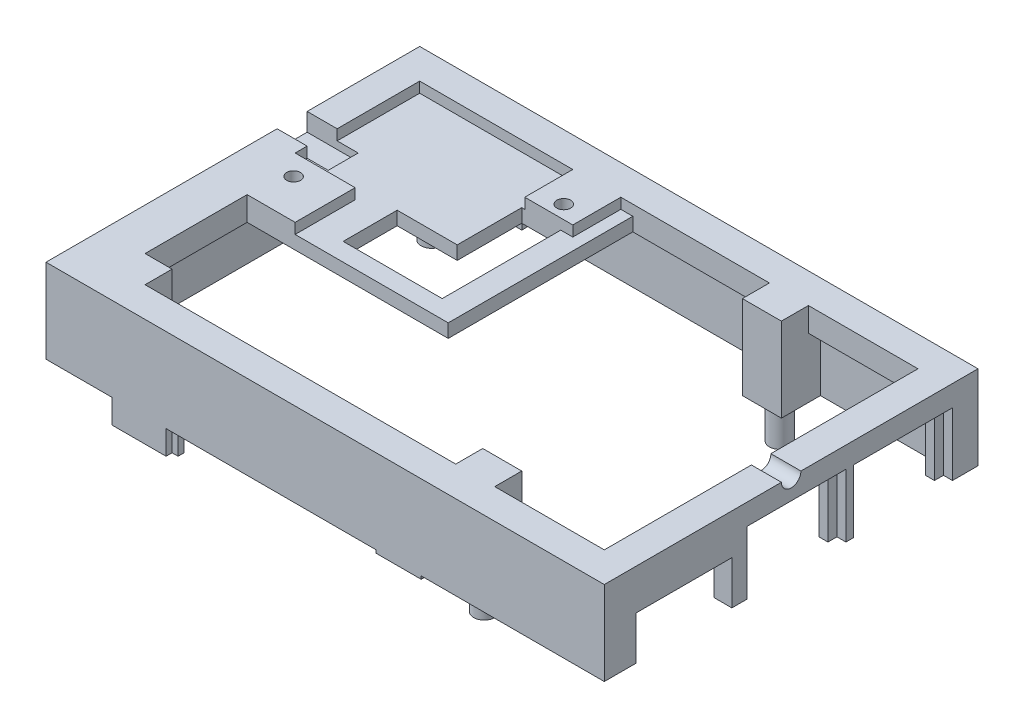
SolidWorks part; units mm, degrees
ref_plane "Front Plane" through (0, 0, 0) normal (0, 0, 1) x (1, 0, 0)
ref_plane "Top Plane" through (0, 0, 0) normal (0, 1, 0) x (1, 0, 0)
ref_plane "Right Plane" through (0, 0, 0) normal (1, 0, 0) x (0, 0, -1)
sketch "Sketch1" plane through (0, 0, 0) normal (0, 1, 0) x (1, 0, 0)
  line L1 (0, 0) -> (93, 0)
  line L2 (0, 0) -> (0, 62.25)
  line L3 (0, 62.25) -> (93, 62.25)
  line L4 (93, 0) -> (93, 62.25)
  line L5 (7, 5) -> (88, 5)
  line L7 (40.5, 57.25) -> (88, 57.25)
  line L8 (88, 5) -> (88, 57.25)
  line L13 (7, 26.5) -> (7, 5)
  line L14 (7, 26.5) -> (40.5, 26.5)
  line L15 (40.5, 26.5) -> (40.5, 57.25)
  dimension "D1" = 93
  dimension "D2" = 62.25
  dimension "D3" = 5
  dimension "D4" = 5
  dimension "D5" = 5
  dimension "D6" = 7
  dimension "D7" = 30.75
  dimension "D8" = 33.5
extrude "Boss-Extrude1" add sketch "Sketch1" along normal blind 4
sketch "Sketch5" plane through (0, 4, 0) normal (0, 1, 0) x (1, 0, 0)
  line L0 (88, 57.25) -> (40.5, 57.25) construction
  line L1 (40.5, 26.5) -> (15, 26.5)
  line L2 (40.5, 26.5) -> (40.5, 57.25)
  line L3 (40.5, 57.25) -> (38.5, 57.25)
  line L4 (5, 36.5) -> (5, 57.25)
  line L5 (5, 36.5) -> (15, 36.5)
  line L6 (15, 36.5) -> (15, 26.5)
  line L7 (30.5, 57.25) -> (5, 57.25)
  line L9 (30.5, 57.25) -> (30.5, 49.25)
  line L10 (30.5, 49.25) -> (38.5, 49.25)
  line L11 (38.5, 57.25) -> (38.5, 49.25)
  dimension "D1" = 35.5
  dimension "D2" = 10
  dimension "D3" = 2
  dimension "D4" = 8
extrude "Cut-Extrude1" cut sketch "Sketch5" against normal blind 1.75
sketch "Sketch6" plane through (0, 2.25, 0) normal (0, 1, 0) x (1, 0, 0)
  line L0 (38.5, 49.25) -> (30.5, 49.25) construction
  line L1 (30, 49.25) -> (36.5, 49.25)
  line L2 (30, 49.25) -> (30, 38.5)
  line L3 (28.25, 29.5) -> (36.5, 29.5)
  line L4 (36.5, 49.25) -> (36.5, 29.5)
  line L5 (36.5, 29.5) -> (20, 29.5)
  line L6 (36.5, 29.5) -> (36.5, 39.375)
  line L7 (30, 38.5) -> (20, 38.5)
  line L8 (20, 29.5) -> (20, 38.5)
  line L9 (20, 29.5) -> (28.25, 29.5)
  line M12 (38.5, 49.25) -> (30.5, 49.25)
  dimension "D1" = 2
  dimension "D2" = 19.75
  dimension "D3" = 16.5
  dimension "D4" = 9
  dimension "D5" = 10
extrude "Cut-Extrude2" cut sketch "Sketch6" against normal through all contours L8 L5 L3 L4 L1 L2 L7 M12
sketch "Sketch7" plane through (0, 4, 0) normal (0, 1, 0) x (1, 0, 0)
  line L0 (30.5, 57.25) -> (5, 57.25) construction
  line L1 (5, 57.25) -> (5, 36.5) construction
  circle A0 centre (8.25, 33) radius 1.15
  circle A1 centre (34.75, 51.5) radius 1.15
  dimension "D2" = 2.3
  dimension "D3" = 2.3
  dimension "D1" = 5.75
  dimension "D4" = 29.75
  dimension "D5" = 3.25
  dimension "D6" = 24.25
extrude "Cut-Extrude3" cut sketch "Sketch7" against normal through all
sketch "Sketch8" plane through (0, 0, 0) normal (0, -1, 0) x (1, 0, 0)
  line L0 (90, -3) -> (90, -59.25)
  line L1 (93, 0) -> (0, 0)
  line L2 (93, 0) -> (93, -62.25)
  line L3 (93, -62.25) -> (0, -62.25)
  line L4 (0, 0) -> (0, -62.25)
  line L5 (90, -59.25) -> (3, -59.25)
  line L6 (3, -3) -> (3, -59.25)
  line L7 (90, -3) -> (3, -3)
  line M11 (0, 0) -> (0, -62.25)
  line M12 (0, -62.25) -> (93, -62.25)
  line M13 (93, -62.25) -> (93, 0)
  line M14 (93, 0) -> (0, 0)
  dimension "D1" = 3
extrude "Boss-Extrude3" add sketch "Sketch8" along normal blind 10 contours L7 L0 L5 L6 M14 M11 M12 M13 | L2 L1 L4 L3
sketch "Sketch16" plane through (0, 4, 0) normal (0, 1, 0) x (1, 0, 0)
  line L0 (90, 3) -> (3, 3) construction
  line L1 (7, 5) -> (11.5, 5) construction
  line L2 (7, 5) -> (7, 9.5) construction
  line L3 (7, 9.5) -> (11.5, 9.5) construction
  line L4 (11.5, 5) -> (11.5, 9.5) construction
  line L5 (11.5, 9.5) -> (5, 9.5)
  line L6 (11.5, 9.5) -> (11.5, 3)
  line L7 (11.5, 3) -> (5, 3)
  line L8 (5, 9.5) -> (5, 3)
  line L9 (0, 31.125) -> (93, 31.125) construction
  line L10 (0, 0) -> (0, 62.25) construction
  line L12 (5, 52.75) -> (5, 59.25)
  line L13 (69.75, 9.5) -> (63.25, 9.5)
  line L14 (69.75, 9.5) -> (69.75, 3)
  line L15 (69.75, 3) -> (63.25, 3)
  line L16 (63.25, 9.5) -> (63.25, 3)
  line L17 (11.5, 59.25) -> (5, 59.25)
  line L18 (11.5, 52.75) -> (11.5, 59.25)
  line L19 (11.5, 52.75) -> (5, 52.75)
  line L20 (11.5, 57.25) -> (11.5, 52.75)
  line L21 (7, 52.75) -> (11.5, 52.75)
  line L22 (63.25, 52.75) -> (63.25, 59.25)
  line L23 (69.75, 59.25) -> (63.25, 59.25)
  line L24 (69.75, 52.75) -> (69.75, 59.25)
  line L25 (69.75, 52.75) -> (63.25, 52.75)
  line L26 (93, 0) -> (93, 62.25) construction
  line M4 (5, 36.5) -> (5, 57.25)
  line M11 (88, 5) -> (7, 5)
  line M12 (7, 5) -> (7, 26.5)
  line M43 (5, 57.25) -> (30.5, 57.25)
  line M47 (38.5, 57.25) -> (88, 57.25)
  dimension "D1" = 4.5
  dimension "D2" = 4.5
  dimension "D3" = 51.75
extrude "Boss-Extrude7" add sketch "Sketch16" against normal up to surface (14 mm away) contours L13 L16 L14 M11 | L16 L15 L14 M11 | L25 L24 L22 M47 | L24 L23 L22 M47 | L18 L17 L12 M43 | L19 L18 M43 M4 | L6 L5 M12 M11 | L5 L8 L7 L6 M11 M12
sketch "Sketch9" plane through (93, 0, 0) normal (1, 0, 0) x (0, 0, -1)
  line L0 (62.25, -10) -> (0, -10) construction
  line L1 (5.25, -10) -> (21.25, -10)
  line L2 (5.25, -10) -> (5.25, -2.75)
  line L3 (5.25, -2.75) -> (21.25, -2.75)
  line L4 (21.25, -10) -> (21.25, -2.75)
  line L5 (0, 4) -> (0, -10) construction
  line L7 (25.25, -10) -> (38.75, -10)
  line L8 (25.25, -10) -> (25.25, -1)
  line L9 (25.25, -1) -> (38.75, -1)
  line L10 (38.75, -10) -> (38.75, -1)
  line L11 (43, -10) -> (56.5, -10)
  line L12 (43, -10) -> (43, -1)
  line L13 (43, -1) -> (56.5, -1)
  line L14 (56.5, -10) -> (56.5, -1)
  dimension "D1" = 7.25
  dimension "D2" = 5.25
  dimension "D3" = 16
  dimension "D4" = 9
  dimension "D5" = 4
  dimension "D6" = 4.25
  dimension "D7" = 13.5
extrude "Cut-Extrude4" cut sketch "Sketch9" against normal blind 3
sketch "Sketch10" plane through (93, 0, 0) normal (1, 0, 0) x (0, 0, -1)
  line L0 (25.25, -10) -> (25.25, -1)
  line L1 (25.25, -1) -> (38.75, -1)
  line L2 (38.75, -1) -> (38.75, -10)
  line L3 (43, -10) -> (43, -1)
  line L4 (43, -1) -> (56.5, -1)
  line L5 (56.5, -1) -> (56.5, -10)
  line L6 (23.75, -10) -> (23.75, 0.5)
  line L7 (23.75, 0.5) -> (40.25, 0.5)
  line L8 (40.25, 0.5) -> (40.25, -10)
  line L9 (41.5, -10) -> (41.5, 0.5)
  line L10 (41.5, 0.5) -> (58, 0.5)
  line L11 (58, 0.5) -> (58, -10)
  line L12 (23.75, -10) -> (25.25, -10)
  line L13 (38.75, -10) -> (40.25, -10)
  line L14 (41.5, -10) -> (43, -10)
  line L15 (56.5, -10) -> (58, -10)
  dimension "D1" = 1.5
extrude "Cut-Extrude5" cut sketch "Sketch10" against normal blind 1.5
sketch "Sketch11" plane through (93, 0, 0) normal (1, 0, 0) x (0, 0, -1)
  line L0 (0, 4) -> (62.25, 4) construction
  arc A0 (29.5, 4) -> (32.75, 4) centre (31.125, 4) ccw
  dimension "D1" = 3.25
extrude "Cut-Extrude6" cut sketch "Sketch11" against normal blind 5 and the other way through all
sketch "Sketch12" plane through (0, -10, 0) normal (0, -1, 0) x (-1, 0, 0)
  line L0 (0, 62.25) -> (-93, 62.25) construction
  line L1 (-20, 62.25) -> (-14, 62.25)
  line L2 (-20, 62.25) -> (-20, 61.25)
  line L3 (-20, 59.25) -> (-14, 59.25)
  line L4 (-14, 62.25) -> (-14, 61.25)
  line L5 (-90, 59.25) -> (-69.75, 59.25) construction
  line L6 (0, 0) -> (0, 62.25) construction
  line L7 (-90, 59.25) -> (-69.75, 59.25) construction
  line L8 (-14, 61.25) -> (-13, 61.25)
  line L10 (-14, 60.25) -> (-13, 60.25)
  line L11 (-13, 61.25) -> (-13, 60.25)
  line L12 (-20, 61.25) -> (-21, 61.25)
  line L14 (-20, 60.25) -> (-21, 60.25)
  line L15 (-21, 61.25) -> (-21, 60.25)
  line L16 (-20, 60.25) -> (-20, 59.25)
  line L17 (-14, 60.25) -> (-14, 59.25)
  dimension "D1" = 14
  dimension "D2" = 6
  dimension "D3" = 1
  dimension "D4" = 1
  dimension "D5" = 1
extrude "Boss-Extrude4" add sketch "Sketch12" along normal blind 1
sketch "Sketch13" plane through (0, -10, 0) normal (0, -1, 0) x (1, 0, 0)
  line L0 (90, -3) -> (69.75, -3) construction
  line L1 (20, -3) -> (11, -3)
  line L2 (20, -3) -> (20, -2)
  line L3 (20, 0) -> (11, 0)
  line L4 (11, -3) -> (11, -2)
  line L5 (93, 0) -> (0, 0) construction
  line L6 (0, 0) -> (0, -62.25) construction
  line L7 (90, -3) -> (69.75, -3) construction
  line L8 (11, -1) -> (10, -1)
  line L10 (11, -2) -> (10, -2)
  line L11 (10, -1) -> (10, -2)
  line L12 (20, -1) -> (21, -1)
  line L14 (20, -2) -> (21, -2)
  line L15 (21, -1) -> (21, -2)
  line L16 (20, -1) -> (20, 0)
  line L17 (11, -1) -> (11, 0)
  dimension "D1" = 11
  dimension "D2" = 9
  dimension "D3" = 1
  dimension "D4" = 1
  dimension "D5" = 1
extrude "Boss-Extrude5" add sketch "Sketch13" along normal blind 4
sketch "Sketch14" plane through (0, 0, 0) normal (-1, 0, 0) x (0, 0, 1)
  line L0 (-62.25, 4) -> (0, 4) construction
  line L1 (-38.5, 4) -> (-43.5, 4)
  line L2 (-38.5, 4) -> (-38.5, 1)
  line L3 (-38.5, 1) -> (-43.5, 1)
  line L4 (-43.5, 4) -> (-43.5, 1)
  dimension "D1" = 12
  dimension "D2" = 5
  dimension "D3" = 3
extrude "Cut-Extrude8" cut sketch "Sketch14" against normal offset from surface (8.5 mm away) 3.5 up to face at (5, 3.125, -44.625) offset beyond the face yes
sketch "Sketch15" plane through (0, -10, 0) normal (0, -1, 0) x (1, 0, 0)
  line L0 (90, -3) -> (69.75, -3) construction
  line L1 (62.5, -3) -> (55, -3)
  line L2 (62.5, -3) -> (62.5, -2)
  line L3 (62.5, 0) -> (55, 0)
  line L4 (55, -3) -> (55, -2)
  line L5 (93, 0) -> (20, 0) construction
  line L6 (21, -2) -> (21, -1) construction
  line L7 (62.5, -2) -> (63.5, -2)
  line L9 (62.5, -1) -> (63.5, -1)
  line L10 (63.5, -2) -> (63.5, -1)
  line L11 (54, -1) -> (55, -1)
  line L12 (54, -1) -> (54, -2)
  line L13 (54, -2) -> (55, -2)
  line L15 (55, -1) -> (55, 0)
  line L16 (62.5, -1) -> (62.5, 0)
  line L17 (93, -5.25) -> (93, 0) construction
  dimension "D1" = 1
  dimension "D2" = 30.5
  dimension "D3" = 7.5
extrude "Boss-Extrude6" add sketch "Sketch15" along normal blind 0.5
sketch "Sketch17" plane through (0, 4, 0) normal (0, 1, 0) x (1, 0, 0)
  line L0 (30.5, 57.25) -> (11.5, 57.25) construction
  line L1 (11.5, 52.75) -> (5, 52.75)
  line L2 (11.5, 52.75) -> (11.5, 57.25)
  line L3 (11.5, 57.25) -> (5, 57.25)
  line L4 (5, 52.75) -> (5, 57.25)
  line L5 (5, 52.75) -> (5, 43.5) construction
extrude "Cut-Extrude9" cut sketch "Sketch17" against normal up to surface (1.75 mm away) up to face at (21.9091, 2.25, -43.5227)
sketch "Sketch18" plane through (0, -10, 0) normal (0, -1, 0) x (-1, 0, 0)
  line L0 (-11.5, 52.75) -> (-11.5, 59.25) construction
  line L1 (-5, 52.75) -> (-11.5, 52.75) construction
  line L2 (-63.25, 52.75) -> (-63.25, 59.25) construction
  line L3 (0, 31.125) -> (-93, 31.125) construction
  line L4 (0, 0) -> (0, 62.25) construction
  line L5 (-93, 40.25) -> (-93, 23.75) construction
  circle A0 centre (-8.5, 55.75) radius 1.75
  circle A1 centre (-66.5, 55.75) radius 1.75
  circle A2 centre (-66.5, 6.5) radius 1.75
  circle A3 centre (-8.5, 6.5) radius 1.75
  dimension "D3" = 3.5
  dimension "D1" = 3
  dimension "D2" = 3
  dimension "D4" = 3.25
extrude "Boss-Extrude8" add sketch "Sketch18" along normal blind 6.4
sketch "Sketch19" plane through (0, -16.4, 0) normal (0, -1, 0) x (1, 0, 0)
  circle A0 centre (8.5, -6.5) radius 1.25
  circle A1 centre (8.5, -55.75) radius 1.25
  circle A2 centre (66.5, -55.75) radius 1.25
  circle A3 centre (66.5, -6.5) radius 1.25
  dimension "D1" = 2.5
extrude "Cut-Extrude10" cut sketch "Sketch19" against normal blind 4
